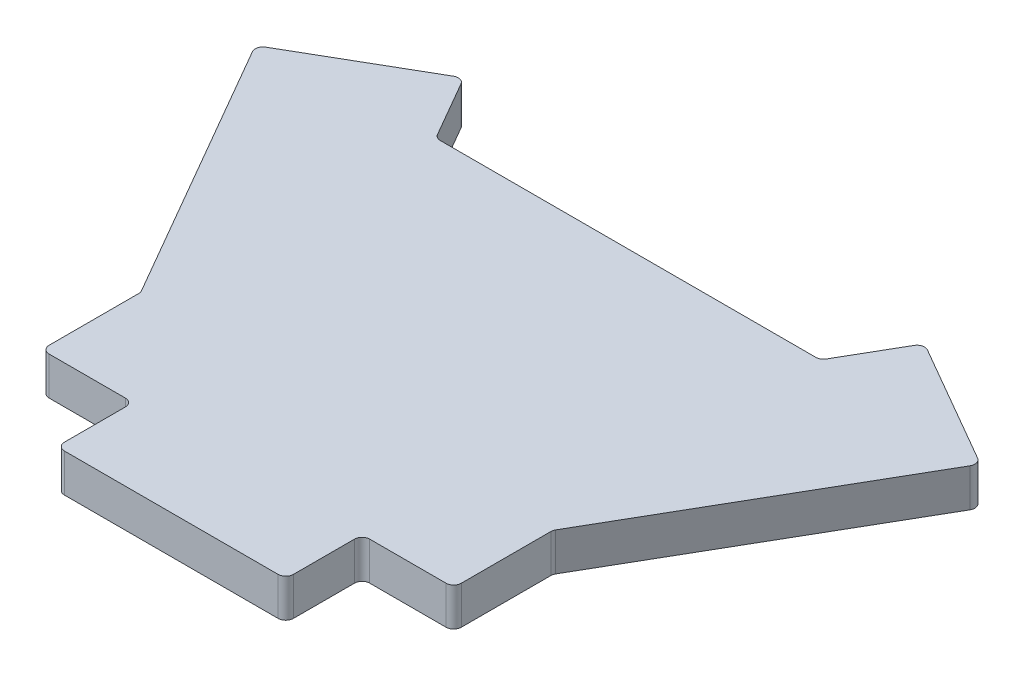
SolidWorks part; units mm, degrees
ref_plane "前基準面" through (0, 0, 0) normal (0, 0, 1) x (1, 0, 0)
ref_plane "上基準面" through (0, 0, 0) normal (0, 1, 0) x (1, 0, 0)
ref_plane "右基準面" through (0, 0, 0) normal (1, 0, 0) x (0, 0, -1)
sketch "草圖1" plane through (0, 0, 0) normal (0, 1, 0) x (1, 0, 0)
  line L0 (0, 0) -> (0, 124.415) construction
  line L1 (15, 0) -> (-15, 0)
  line L2 (-15, 0) -> (-15, 10)
  line L3 (-15, 10) -> (-27, 10)
  line L4 (-27, 10) -> (-27, 23)
  line L5 (-27, 23) -> (-47.5, 58.507)
  line L6 (-47.5, 58.507) -> (-30.1795, 68.507)
  line L7 (-30.1795, 68.507) -> (-25.1795, 59.8468)
  line L8 (-25.1795, 59.8468) -> (25.1795, 59.8468)
  line L9 (30.1795, 68.507) -> (25.1795, 59.8468)
  line L10 (47.5, 58.507) -> (30.1795, 68.507)
  line L11 (27, 23) -> (47.5, 58.507)
  line L12 (27, 10) -> (27, 23)
  line L13 (15, 10) -> (27, 10)
  line L14 (15, 0) -> (15, 10)
  point P12 (0, 59.8468)
  dimension "D1" = 30
  dimension "D2" = 54
  dimension "D3" = 30
  dimension "D4" = 10
  dimension "D5" = 13
  dimension "D6" = 95
  dimension "D7" = 10
  dimension "D8" = 20
extrude "填料-伸長1" add sketch "草圖1" along normal blind 5
fillet "圓角1" radius 1 14 edges at (47.5, 2.5, -58.507) (30.1795, 2.5, -68.507) (25.1795, 2.5, -59.8468) (-25.1795, 2.5, -59.8468) (-30.1795, 2.5, -68.507) (-47.5, 2.5, -58.507) (-27, 2.5, -23) (-15, 2.5, 0) (-27, 2.5, -10) (-15, 2.5, -10) (27, 2.5, -23) (27, 2.5, -10) (15, 2.5, -10) (15, 2.5, 0)
